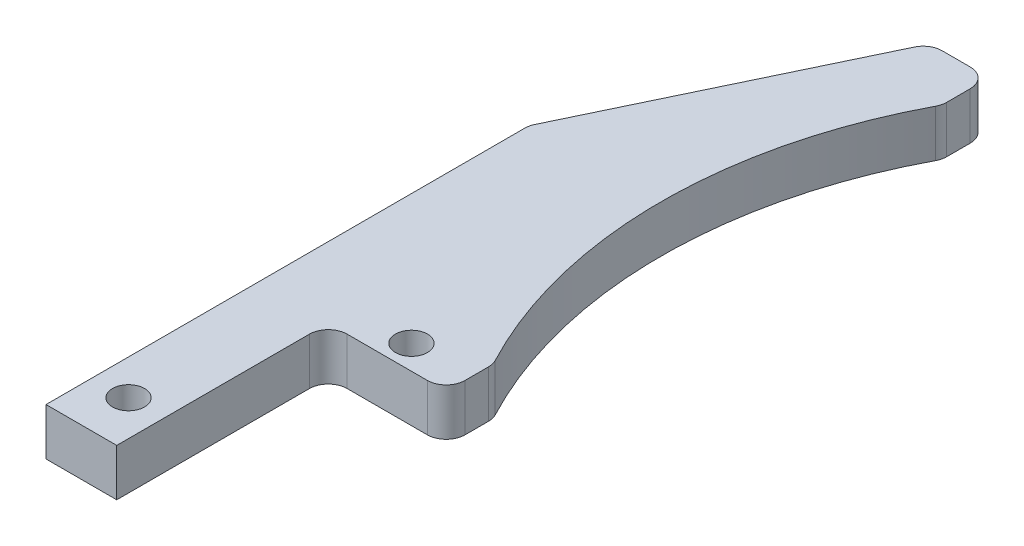
SolidWorks part; units mm, degrees
material "PET"
ref_plane "Front Plane" through (0, 0, 0) normal (0, 0, 1) x (1, 0, 0)
ref_plane "Top Plane" through (0, 0, 0) normal (0, 1, 0) x (1, 0, 0)
ref_plane "Right Plane" through (0, 0, 0) normal (1, 0, 0) x (0, 0, -1)
sketch "Sketch1" plane through (0, 0, 0) normal (0, 1, 0) x (1, 0, 0)
  line L0 (0, 0) -> (9.525, 0)
  line L1 (9.525, 0) -> (9.525, 28.4897)
  line L2 (9.525, 28.4897) -> (25.4, 28.4897)
  line L3 (25.4, 28.4897) -> (25.4, 34.8397)
  line L5 (0, 65.0448) -> (0, 0)
  line L6 (25.4, 101.6) -> (17.4625, 101.6)
  line L7 (17.4625, 101.6) -> (0, 65.0448)
  line L8 (25.4, 95.25) -> (25.4, 101.6)
  arc A0 (25.4, 34.8397) -> (25.4, 95.25) centre (81.256, 65.0448) cw
  dimension "D4" = 6.35
  dimension "D5" = 63.5
  dimension "D1" = 9.525
  dimension "D2" = 25.4
  dimension "D3" = 101.6
extrude "Boss-Extrude1" add sketch "Sketch1" along normal blind 6.35 contours L2 L3 A0 L8 L6 L7 L5 L0 L1
ref_plane "Plane1" through (0, 3.175, 0) normal (0, 1, 0) x (1, 0, 0)
sketch "Sketch5" plane through (0, 3.175, 0) normal (0, 1, 0) x (1, 0, 0)
  line L1 (0, 0) -> (9.525, 0) construction
  circle A1 centre (4.7625, 6.35) radius 2.159
  circle A2 centre (17.4625, 31.75) radius 2.159
  point P6 (4.7625, 0)
  dimension "D1" = 6.35
  dimension "D2" = 25.4
  dimension "D3" = 4.318
  dimension "D4" = 4.318
  dimension "D5" = 12.7
extrude "Cut-Extrude2" cut sketch "Sketch5" against normal through all both and the other way through all contours A2 | A1
fillet "Fillet1" radius 2.54 7 edges at (25.4, 3.175, -101.6) (17.4625, 3.175, -101.6) (25.4, 3.175, -95.25) (25.4, 3.175, -34.8397) (25.4, 3.175, -28.4897) (9.525, 3.175, -28.4897) (0, 3.175, -65.0448)
